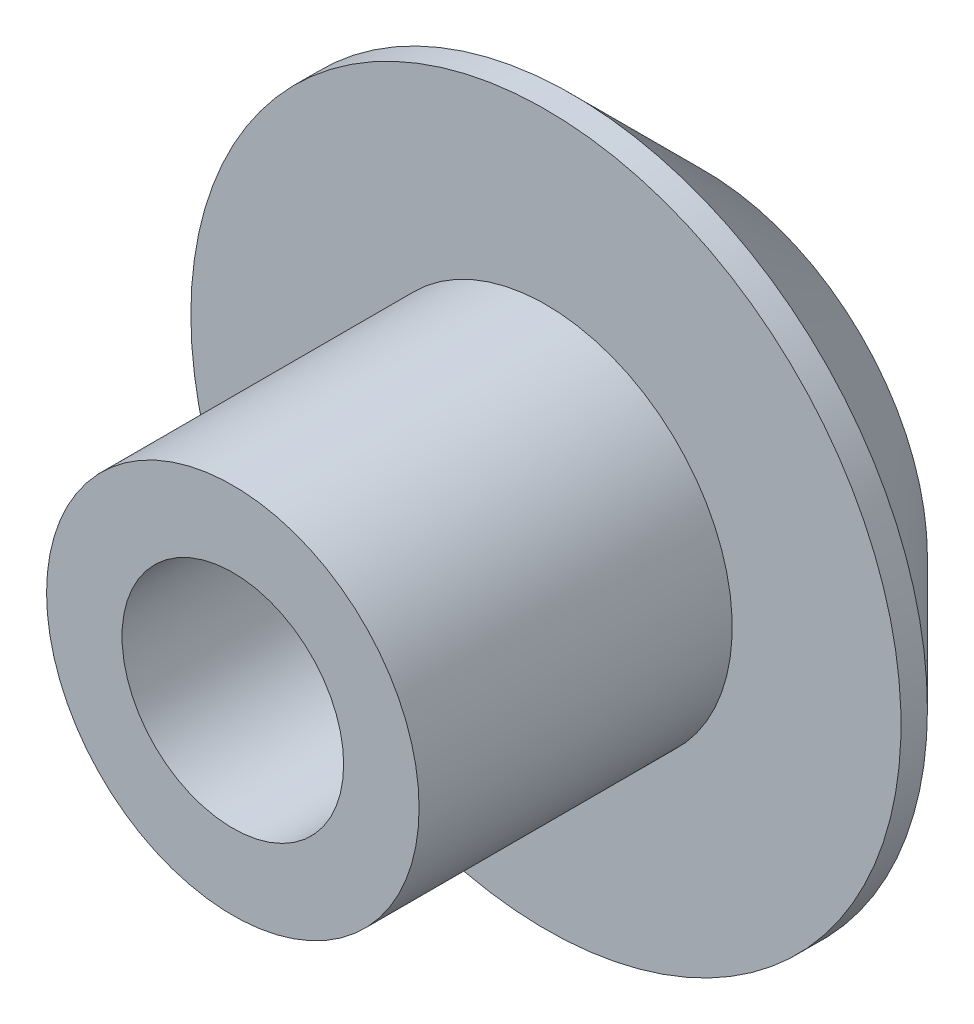
SolidWorks part; units mm, degrees
ref_plane "Plano frontal" through (0, 0, 0) normal (0, 0, 1) x (1, 0, 0)
ref_plane "Plano superior" through (0, 0, 0) normal (0, 1, 0) x (1, 0, 0)
ref_plane "Plano direito" through (0, 0, 0) normal (1, 0, 0) x (0, 0, -1)
sketch "Esboço1" plane through (0, 0, 0) normal (0, 0, 1) x (1, 0, 0)
  circle A0 centre (0, 0) radius 1.975
  circle A1 centre (0, 0) radius 1.175
  dimension "D1" = 3.95
  dimension "D2" = 2.35
extrude "Ressalto-extrusão1" add sketch "Esboço1" along normal blind 5
sketch "Esboço2" plane through (0, 0, 0) normal (0, 0, -1) x (-1, 0, 0)
  circle A0 centre (0, 0) radius 3.765
  circle A1 centre (0, 0) radius 1.175
  dimension "D1" = 7.53
extrude "Ressalto-extrusão2" add sketch "Esboço2" against normal blind 1.68
chamfer "Chanfro1" distance 1.4 angle 45 1 edges at (-3.765, 0, 0)
